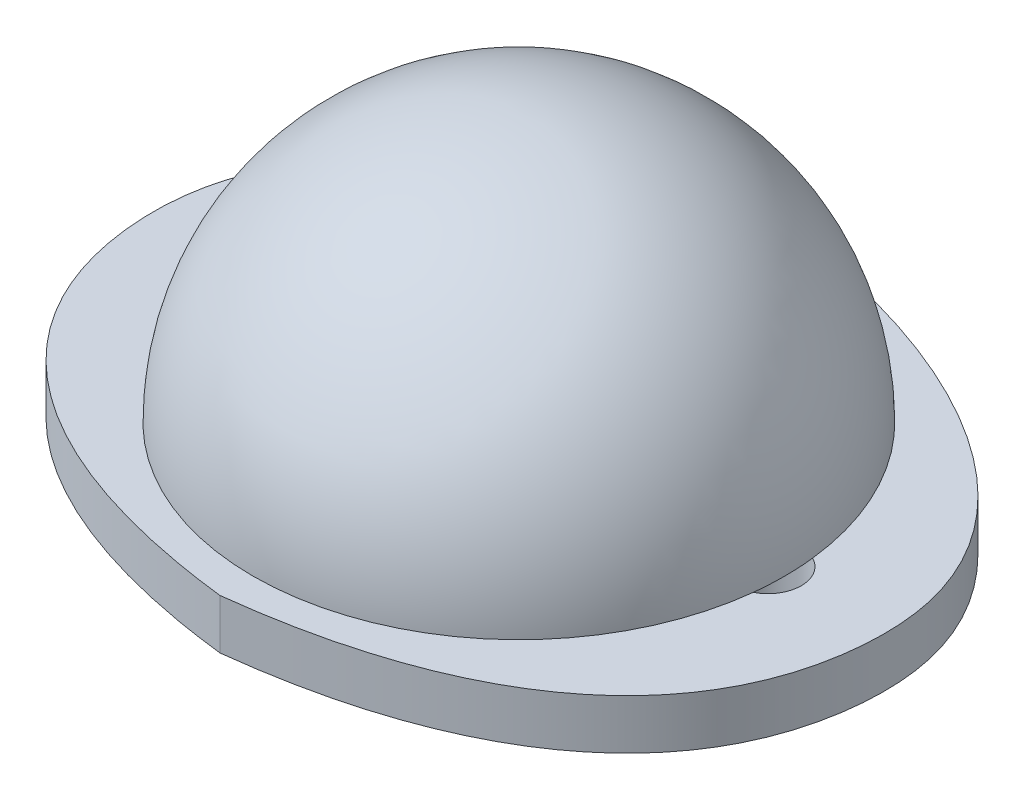
SolidWorks part; units mm, degrees
ref_plane "前基準面" through (0, 0, 0) normal (0, 0, 1) x (1, 0, 0)
ref_plane "上基準面" through (0, 0, 0) normal (0, 1, 0) x (1, 0, 0)
ref_plane "右基準面" through (0, 0, 0) normal (1, 0, 0) x (0, 0, -1)
sketch "草圖3" plane through (0, 0, 0) normal (0, 1, 0) x (1, 0, 0)
  line L0 (0, 0) -> (-45.1188, 0) construction
  line L1 (0, 0) -> (0, -26.1748) construction
  line L2 (-22, -7.6907) -> (-22, 7.3373) construction
  circle A0 centre (0, 0) radius 10
  spline S0 degree 3 poles (0, 18) (-10.982, 16.1459) (-22.2488, 9.4015) (-21.9138, -9.8584) (-12.8564, -16.5043) (0, -18) knots 0 0 0 0 0.44106 0.54106 1 1 1 1
  spline S1 degree 3 poles (0, 18) (10.982, 16.1459) (22.2488, 9.4015) (21.9138, -9.8584) (12.8564, -16.5043) (0, -18) knots 0 0 0 0 0.44106 0.54106 1 1 1 1
  point P3 (0, 0)
  point P4 (-22, 0)
  point P13 (0, 0)
  point P14 (0, 0)
  dimension "D1" = 20
  dimension "D2" = 18
  dimension "D3" = 22
  dimension "D4" = 18
extrude "填料-伸長1" add sketch "草圖3" along normal blind 3
sketch "草圖4" plane through (0, 0, 0) normal (0, 0, 1) x (1, 0, 0)
  line L0 (10, 3) -> (-10, 3) construction
  line L1 (22, 3) -> (0, 3) construction
  line L2 (0, 3) -> (0, 19) construction
  line L3 (0, 3) -> (16, 3)
  line L4 (0, 19) -> (0, 3)
  arc A0 (16, 3) -> (0, 19) centre (0, 3) ccw
  dimension "D1" = 16
revolve "旋轉1" add sketch "草圖4" angle 360 about L2
sketch "草圖5" plane through (0, 0, 0) normal (0, -1, 0) x (1, 0, 0)
  line L0 (-22, 0) -> (22, 0) construction
  circle A0 centre (-15, 0) radius 2
  circle A1 centre (15, 0) radius 2
  spline S0 degree 3 poles (0, -18) (-10.982, -16.1459) (-22.2488, -9.4015) (-21.9138, 9.8584) (-12.8564, 16.5043) (0, 18) knots 0 0 0 0 0.44106 0.54106 1 1 1 1 construction
  spline S1 degree 3 poles (0, 18) (12.8564, 16.5043) (21.9138, 9.8584) (22.2488, -9.4015) (10.982, -16.1459) (0, -18) knots 0 0 0 0 0.45894 0.55894 1 1 1 1 construction
  dimension "D3" = 4
  dimension "D4" = 4
  dimension "D1" = 30
  dimension "D2" = 15
extrude "除料-伸長1" cut sketch "草圖5" against normal blind 3
